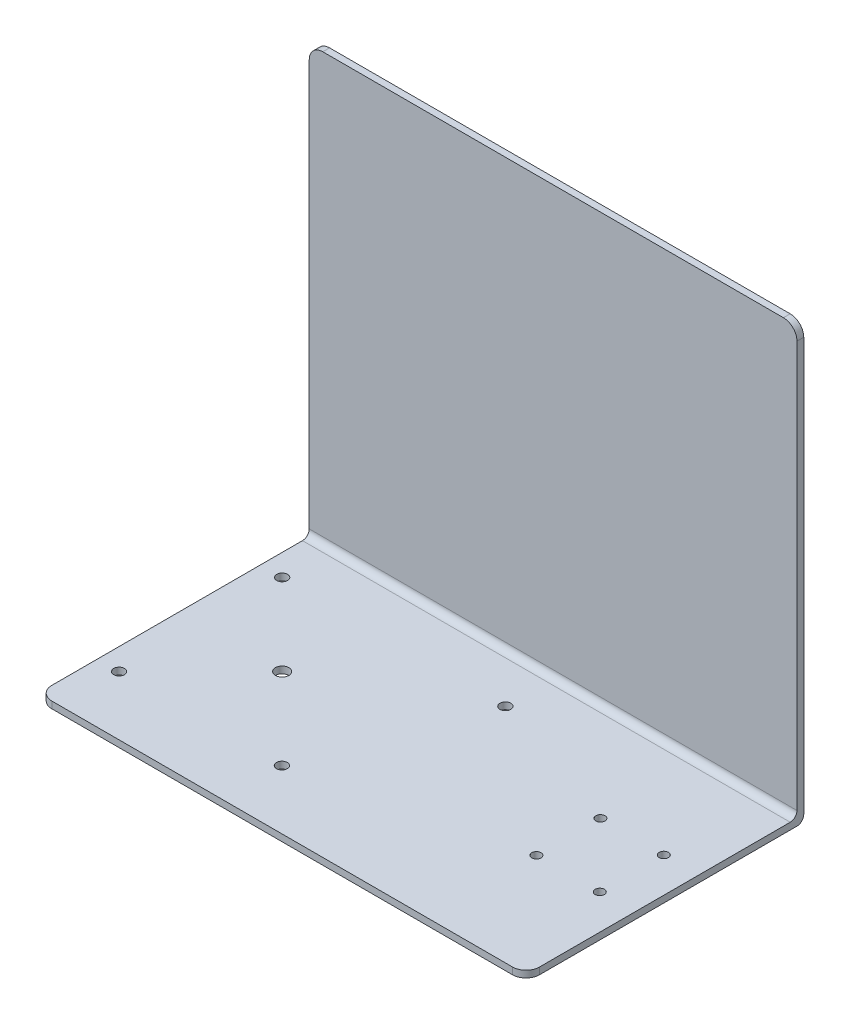
SolidWorks part; units mm, degrees
ref_plane "Front Plane" through (0, 0, 0) normal (0, 0, 1) x (1, 0, 0)
ref_plane "Top Plane" through (0, 0, 0) normal (0, 1, 0) x (1, 0, 0)
ref_plane "Right Plane" through (0, 0, 0) normal (1, 0, 0) x (0, 0, -1)
sketch "Sketch2" plane through (0, 0, 0) normal (0, 0, 1) x (1, 0, 0)
  line L1 (-114.3, -101.6) -> (114.3, -101.6)
  line L2 (-114.3, -101.6) -> (-114.3, 101.6)
  line L3 (-114.3, 101.6) -> (114.3, 101.6)
  line L4 (114.3, -101.6) -> (114.3, 101.6)
  line L5 (-114.3, -101.6) -> (114.3, 101.6) construction
  line L6 (-114.3, 101.6) -> (114.3, -101.6) construction
  point P0 (0, 0)
  dimension "D1" = 228.6
  dimension "D2" = 203.2
extrude "Boss-Extrude1" add sketch "Sketch2" along normal blind 3.175
sketch "Sketch3" plane through (0, 0, 3.175) normal (0, 0, 1) x (1, 0, 0)
  line L0 (114.3, -101.6) -> (114.3, 101.6) construction
  line L1 (-114.3, -101.6) -> (114.3, -101.6)
  line L2 (-114.3, -101.6) -> (-114.3, -98.425)
  line L3 (-114.3, -98.425) -> (114.3, -98.425)
  line L4 (114.3, -101.6) -> (114.3, -98.425)
  dimension "D1" = 3.175
extrude "Boss-Extrude2" add sketch "Sketch3" along normal blind 127
fillet "Fillet1" radius 3.175 2 edges at (0, -101.6, 0) (0, -98.425, 3.175)
fillet "Fillet2" radius 6.35 4 edges at (114.3, -100.0125, 130.175) (-114.3, -100.0125, 130.175) (114.3, 101.6, 1.5875) (-114.3, 101.6, 1.5875)
sketch "Sketch4" plane through (0, -98.425, 0) normal (0, 1, 0) x (1, 0, 0)
  line L0 (-114.3, -123.825) -> (-114.3, -6.35) construction
  line L1 (107.95, -130.175) -> (-107.95, -130.175) construction
  circle A0 centre (-104.14, -26.035) radius 2.54
  circle A1 centre (-104.14, -102.4636) radius 2.54
  circle A2 centre (0.4826, -26.035) radius 2.54
  circle A3 centre (-27.8257, -102.4636) radius 2.54
  circle A6 centre (68.25, -79.2493) radius 2.15
  circle A7 centre (97.95, -79.2493) radius 2.15
  circle A8 centre (68.25, -49.2493) radius 2.15
  circle A9 centre (97.95, -49.2493) radius 2.15
  circle A10 centre (-65.9257, -64.2493) radius 3.175
  dimension "D1" = 5.08
  dimension "D2" = 5.08
  dimension "D3" = 5.08
  dimension "D4" = 5.08
  dimension "D5" = 6.35
  dimension "D6" = 4.3
  dimension "D7" = 4.3
  dimension "D8" = 4.3
  dimension "D9" = 4.3
  dimension "D15" = 27.7114
  dimension "D10" = 10.16
  dimension "D11" = 114.7826
  dimension "D12" = 182.55
  dimension "D13" = 212.25
  dimension "D14" = 48.3743
  dimension "D16" = 104.14
  dimension "D17" = 65.9257
  dimension "D18" = 50.9257
  dimension "D19" = 80.9257
extrude "Cut-Extrude1" cut sketch "Sketch4" against normal through all
